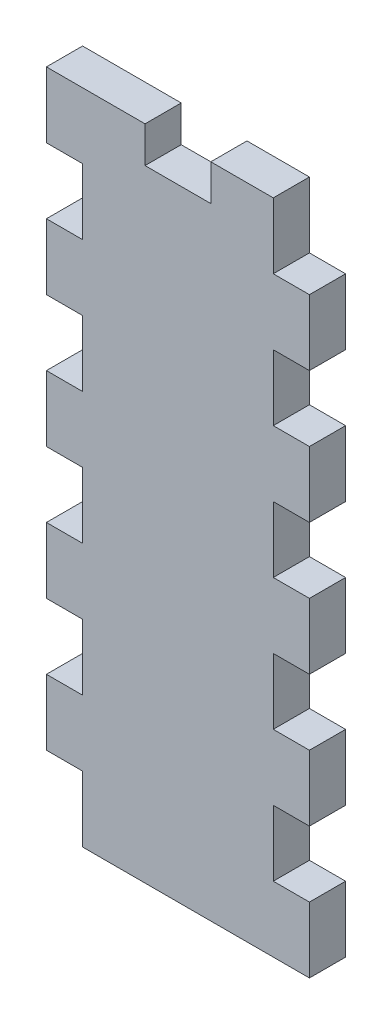
SolidWorks part; units mm, degrees
material "ﾁｰｸ材"
ref_plane "正面" through (0, 0, 0) normal (0, 0, 1) x (1, 0, 0)
ref_plane "平面" through (0, 0, 0) normal (0, 1, 0) x (1, 0, 0)
ref_plane "右側面" through (0, 0, 0) normal (1, 0, 0) x (0, 0, -1)
sketch "ｽｹｯﾁ1" plane through (0, 0, 0) normal (0, 0, 1) x (1, 0, 0)
  line L1 (20, 50) -> (-20, 50)
  line L2 (20, 50) -> (20, -50)
  line L3 (20, -50) -> (-20, -50)
  line L4 (-20, 50) -> (-20, -50)
  line L5 (20, 50) -> (-20, -50) construction
  line L6 (20, -50) -> (-20, 50) construction
  point P0 (0, 0)
  dimension "D1" = 40
  dimension "D2" = 100
extrude "ﾎﾞｽ - 押し出し1" add sketch "ｽｹｯﾁ1" along normal blind 5.5
sketch "ｽｹｯﾁ2" plane through (0, 0, 5.5) normal (0, 0, 1) x (1, 0, 0)
  line L0 (20, -50) -> (20, 50) construction
  line L1 (-20, -50) -> (-14.5, -50)
  line L2 (-20, -50) -> (-20, -40)
  line L3 (-20, -40) -> (-14.5, -40)
  line L4 (-14.5, -50) -> (-14.5, -40)
  line L5 (20, -40) -> (14.5, -40)
  line L6 (20, -40) -> (20, -30)
  line L7 (20, -30) -> (14.5, -30)
  line L8 (14.5, -40) -> (14.5, -30)
  line L9 (-20, -30) -> (-20, -20)
  line L10 (-20, -30) -> (-14.5, -30)
  line L11 (-14.5, -30) -> (-14.5, -20)
  line L12 (-20, -20) -> (-14.5, -20)
  line L13 (20, -20) -> (20, -10)
  line L14 (20, -20) -> (14.5, -20)
  line L15 (14.5, -20) -> (14.5, -10)
  line L16 (20, -10) -> (14.5, -10)
  line L17 (-20, -10) -> (-20, 0)
  line L18 (-20, -10) -> (-14.5, -10)
  line L19 (-14.5, -10) -> (-14.5, 0)
  line L20 (-20, 0) -> (-14.5, 0)
  line L21 (20, 0) -> (20, 10)
  line L22 (20, 0) -> (14.5, 0)
  line L23 (14.5, 0) -> (14.5, 10)
  line L24 (20, 10) -> (14.5, 10)
  line L25 (-20, 10) -> (-20, 20)
  line L26 (-20, 10) -> (-14.5, 10)
  line L27 (-14.5, 10) -> (-14.5, 20)
  line L28 (-20, 20) -> (-14.5, 20)
  line L29 (20, 20) -> (20, 30)
  line L30 (20, 20) -> (14.5, 20)
  line L31 (14.5, 20) -> (14.5, 30)
  line L32 (20, 30) -> (14.5, 30)
  line L33 (-20, 30) -> (-20, 40)
  line L34 (-20, 30) -> (-14.5, 30)
  line L35 (-14.5, 30) -> (-14.5, 40)
  line L36 (-20, 40) -> (-14.5, 40)
  line L37 (20, 40) -> (20, 50)
  line L38 (20, 40) -> (14.5, 40)
  line L39 (14.5, 40) -> (14.5, 50)
  line L40 (20, 50) -> (14.5, 50)
  line L41 (-20, -50) -> (-20, -30) construction
  dimension "D1" = 5.5
  dimension "D2" = 5.5
  dimension "D3" = 10
  dimension "D4" = 10
  dimension "D6" = 20
  dimension "D5" = 5
extrude "ｶｯﾄ - 押し出し1" cut sketch "ｽｹｯﾁ2" against normal through all
sketch "ｽｹｯﾁ3" plane through (0, 0, 5.5) normal (0, 0, 1) x (1, 0, 0)
  line L0 (14.5, 50) -> (-20, 50) construction
  line L1 (-5, 44.5) -> (5, 44.5)
  line L2 (-5, 44.5) -> (-5, 50)
  line L3 (-5, 50) -> (5, 50)
  line L4 (5, 44.5) -> (5, 50)
  line L5 (-5, 44.5) -> (5, 50) construction
  line L6 (-5, 50) -> (5, 44.5) construction
  point P0 (0, 47.25)
  dimension "D1" = 5.5
  dimension "D2" = 10
extrude "ｶｯﾄ - 押し出し2" cut sketch "ｽｹｯﾁ3" against normal through all
